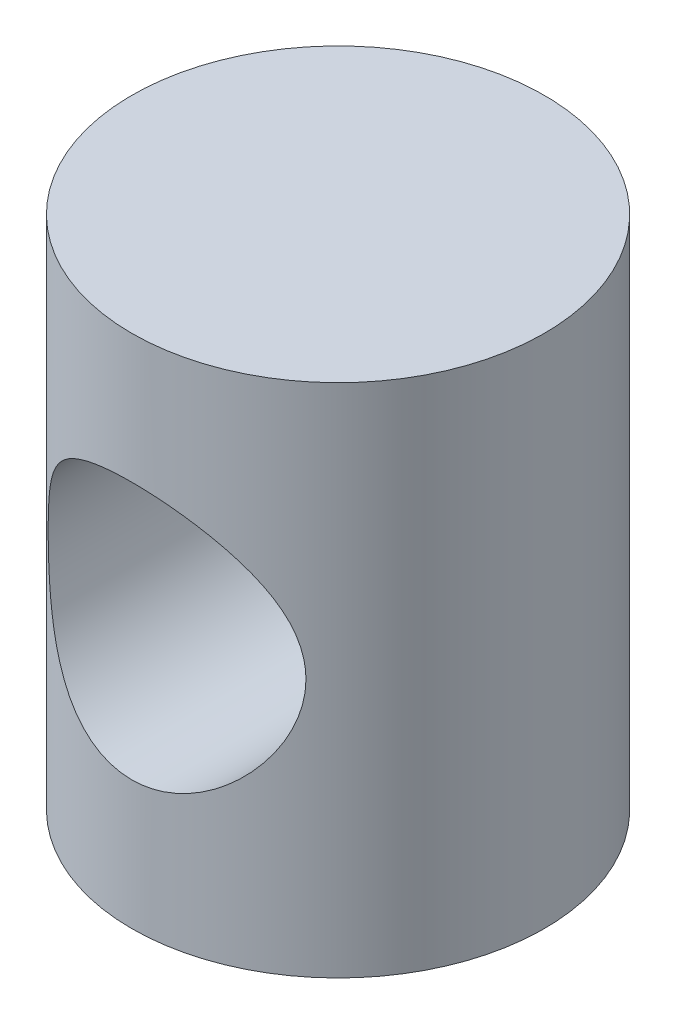
SolidWorks part; units mm, degrees
material "5086-H32, Стержень (SS)"
ref_plane "Спереди" through (0, 0, 0) normal (0, 0, 1) x (1, 0, 0)
ref_plane "Сверху" through (0, 0, 0) normal (0, 1, 0) x (1, 0, 0)
ref_plane "Справа" through (0, 0, 0) normal (1, 0, 0) x (0, 0, -1)
sketch "Эскиз1" plane through (0, 0, 0) normal (0, 1, 0) x (1, 0, 0)
  circle A0 centre (0, 0) radius 4
  dimension "D1" = 8
extrude "Бобышка-Вытянуть1" add sketch "Эскиз1" along normal blind 10
ref_plane "Плоскость2" through (0, 0, 4) normal (0, 0, 1) x (1, 0, 0)
sketch "Эскиз6" plane through (0, 0, 4) normal (0, 0, 1) x (1, 0, 0)
  point P0 (0, 5)
  dimension "D1" = 5
hole_wizard "Отверстие обработанное метчиком M61" positions "Трехмерный эскиз5" profile "Эскиз13" tap size "M6" standard "ISO" end condition through all
sketch3d "Трехмерный эскиз5"
  point P0 (0, 5, 4)
  dimension "D1" = 0
sketch "Эскиз13" plane through (0, 5, 4) normal (1, 0, 0) x (0, -1, 0)
  line L0 (0, 0) -> (0, 8)
  line L1 (0, 8) -> (2.5, 8)
  line L2 (2.5, 8) -> (2.5, 0)
  line L5 (2.5, 0) -> (0, 0)
  line L11 (0, -6.35) -> (0, 107.95) construction
  dimension "Диаметр проходного сверла" = 5
  dimension "Глубина проходного сверла" = 8
cosmetic thread "Отверстие резьбы1" parameters "D2"=6
